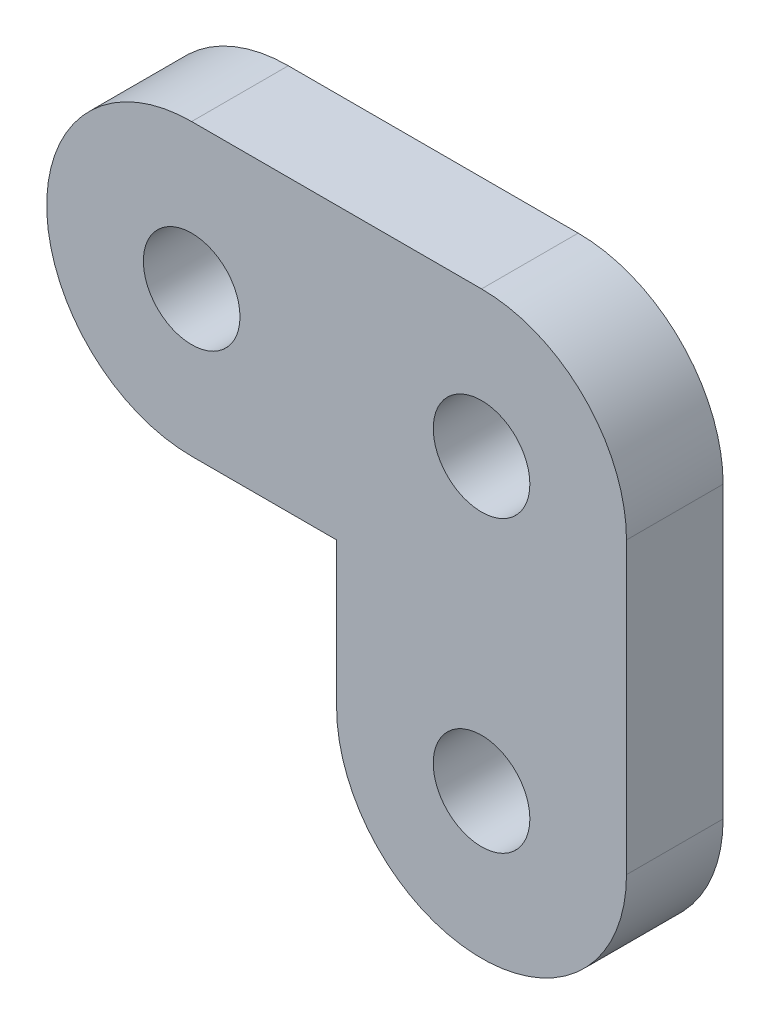
SolidWorks part; units mm, degrees
ref_plane "Alzado" through (0, 0, 0) normal (0, 0, 1) x (1, 0, 0)
ref_plane "Planta" through (0, 0, 0) normal (0, 1, 0) x (1, 0, 0)
ref_plane "Vista lateral" through (0, 0, 0) normal (1, 0, 0) x (0, 0, -1)
sketch "Model" plane through (0, 0, 0) normal (0, 0, 1) x (1, 0, 0)
  line L0 (149.3421, 211.824) -> (158.3421, 211.824)
  line L1 (153.8421, 202.824) -> (149.3421, 202.824)
  line L2 (162.8421, 198.324) -> (162.8421, 207.324)
  line L3 (153.8421, 198.324) -> (153.8421, 202.824)
  arc A0 (149.3421, 211.824) -> (149.3421, 202.824) centre (149.3421, 207.324) ccw
  arc A1 (162.8421, 207.324) -> (158.3421, 211.824) centre (158.3421, 207.324) ccw
  circle A2 centre (149.3421, 207.324) radius 1.5
  circle A3 centre (158.3421, 207.324) radius 1.5
  arc A4 (153.8421, 198.324) -> (162.8421, 198.324) centre (158.3421, 198.324) ccw
  circle A5 centre (158.3421, 198.324) radius 1.5
extrude "Saliente-Extruir1" add sketch "Model" along normal blind 3
